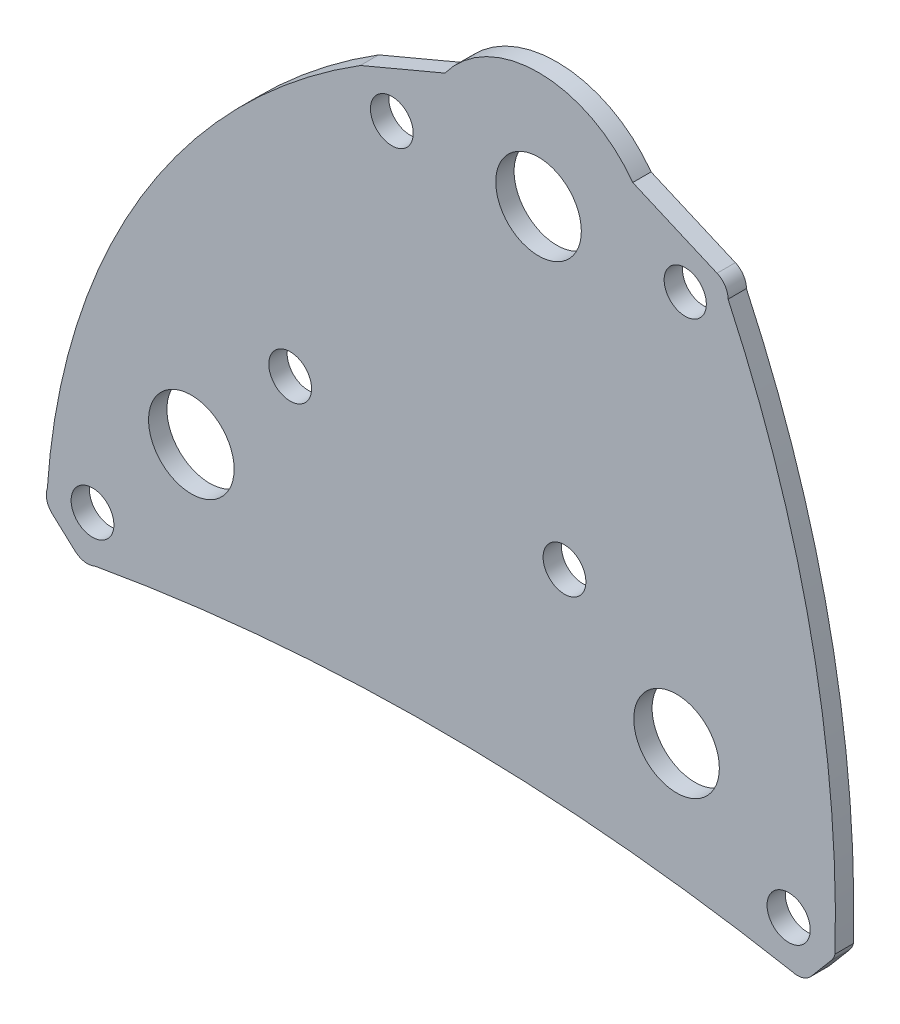
SolidWorks part; units mm, degrees
ref_plane "Front Plane" through (0, 0, 0) normal (0, 0, 1) x (1, 0, 0)
ref_plane "Top Plane" through (0, 0, 0) normal (0, 1, 0) x (1, 0, 0)
ref_plane "Right Plane" through (0, 0, 0) normal (1, 0, 0) x (0, 0, -1)
sketch "Sketch1" plane through (0, 0, 0) normal (0, 0, 1) x (1, 0, 0)
  line L1 (-65, 55) -> (65, 55)
  line L2 (-65, 55) -> (-65, -55)
  line L3 (-65, -55) -> (65, -55)
  line L4 (65, 55) -> (65, -55)
  line L5 (-65, 55) -> (65, -55) construction
  line L6 (-65, -55) -> (65, 55) construction
  point P0 (0, 0)
  dimension "D1" = 130
  dimension "D2" = 110
extrude "Boss-Extrude1" add sketch "Sketch1" along normal blind 3
sketch "Sketch2" plane through (0, 0, 3) normal (0, 0, 1) x (1, 0, 0)
  line L0 (-59.4758, -53.6071) -> (-63.1984, -50.2124)
  line L4 (-65, 55) -> (-65, -55)
  line L5 (-12.8009, 38.5237) -> (1.0389, 44.361)
  line L6 (-65, -55) -> (65, -55)
  line L7 (65, -55) -> (65, 55)
  line L8 (45.555, 38.2632) -> (31.7679, 44.2239)
  line L9 (60.9918, -53.6031) -> (64.2426, -49.7541)
  line L10 (65, 55) -> (-65, 55)
  arc A1 (-64.0095, -47.0073) -> (-63.1984, -50.2124) centre (-61.177, -47.9957) ccw
  arc A2 (-59.4758, -53.6071) -> (-56.2096, -54.12) centre (-57.4543, -51.3904) ccw
  arc A7 (31.7679, 44.2239) -> (1.0389, 44.361) centre (16.3535, 33.1155) ccw
  arc A8 (47.3644, 35.4961) -> (45.555, 38.2632) centre (44.3645, 35.5095) ccw
  arc A11 (64.2426, -49.7541) -> (64.8583, -48.557) centre (61.9506, -47.8184) ccw
  arc A12 (57.8198, -54.5354) -> (60.9918, -53.6031) centre (58.6999, -51.6674) ccw
  arc A13 (-64.0095, -47.0073) -> (-12.8009, 38.5237) centre (45.2187, -54.3086) cw
  arc A19 (47.3644, 35.4961) -> (64.8583, -48.557) centre (-122.3879, -43.6813) cw
  arc A20 (57.8198, -54.5354) -> (-56.2096, -54.12) centre (-0.332, -366.4705) ccw
extrude "Cut-Extrude1" cut sketch "Sketch2" against normal blind 10
sketch "Sketch3" plane through (0, 0, 3) normal (0, 0, 1) x (1, 0, 0)
  circle A0 centre (16.3535, 33.1155) radius 7
  circle A1 centre (40.3533, 33.0084) radius 3.4513
  circle A2 centre (-7.6463, 33.2226) radius 3.5
  circle A3 centre (-40.4489, -29.0038) radius 7
  circle A4 centre (-56.6204, -46.7375) radius 3.5
  circle A5 centre (-24.2775, -11.2701) radius 3.5
  circle A6 centre (20.5983, -16.1904) radius 3.5
  circle A7 centre (38.9338, -31.6762) radius 7
  circle A8 centre (57.2693, -47.162) radius 3.5339
  dimension "D1" = 14
  dimension "D2" = 14
  dimension "D3" = 14
extrude "Cut-Extrude2" cut sketch "Sketch3" against normal blind 10
